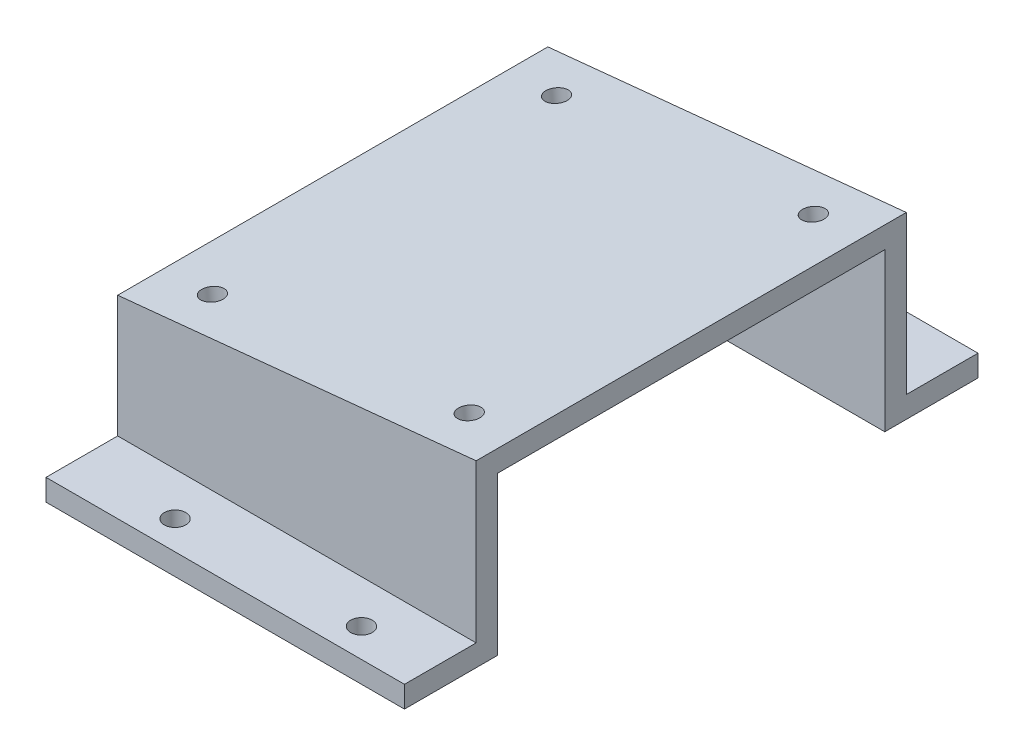
SolidWorks part; units mm, degrees
ref_plane "前视基准面" through (0, 0, 0) normal (0, 0, 1) x (1, 0, 0)
ref_plane "上视基准面" through (0, 0, 0) normal (0, 1, 0) x (1, 0, 0)
ref_plane "右视基准面" through (0, 0, 0) normal (1, 0, 0) x (0, 0, -1)
other "Configuration Table"
sketch "草图4" plane through (0, 0, 0) normal (0, 0, 1) x (1, 0, 0)
  line L0 (0, 0) -> (50, 0)
  line L1 (0, 0) -> (0, 20)
  line L2 (0, 20) -> (50, 25)
  line L3 (50, 25) -> (50, 0)
  dimension "D1" = 50
  dimension "D2" = 25
  dimension "D3" = 20
extrude "凸台-拉伸3" add sketch "草图4" along normal blind 3
sketch "草图5" plane through (0, 0, 3) normal (0, 0, 1) x (1, 0, 0)
  line L0 (0, 20) -> (0, 17)
  line L1 (0, 20) -> (0, 0) construction
  line L2 (0, 17) -> (50, 22)
  line L3 (50, 0) -> (50, 25) construction
  line L4 (50, 22) -> (50, 25)
  line L5 (50, 25) -> (0, 20)
  dimension "D1" = 3
  dimension "D2" = 3
extrude "凸台-拉伸4" add sketch "草图5" along normal blind 54
sketch "草图7" plane through (0, 0, 57) normal (0, 0, 1) x (1, 0, 0)
  line L1 (0, 17) -> (0, 0) construction
  line L2 (0, 0) -> (50, 0) construction
  line L3 (50, 0) -> (50, 22) construction
  line L4 (50, 25) -> (0, 20) construction
  line L5 (0, 20) -> (0, 17) construction
  line L7 (50, 22) -> (50, 25) construction
  line L9 (0, 17) -> (0, 0)
  line L10 (0, 0) -> (50, 0)
  line L11 (50, 0) -> (50, 22)
  line L12 (50, 25) -> (0, 20)
  line L13 (0, 20) -> (0, 17)
  line L15 (50, 22) -> (50, 25)
  line L16 (0, 17) -> (0, 0)
  line L17 (50, 0) -> (50, 22)
sketch "草图8" plane through (0, 0, 57) normal (0, 0, 1) x (1, 0, 0)
  line L0 (0, 20) -> (50, 25)
  line L1 (50, 25) -> (50, 0)
  line L2 (50, 0) -> (0, 0)
  line L3 (0, 0) -> (0, 20)
extrude "凸台-拉伸5" add sketch "草图8" along normal blind 3
sketch "草图9" plane through (0, 0, 60) normal (0, 0, 1) x (1, 0, 0)
  line L0 (0, 0) -> (0, 3)
  line L1 (0, 20) -> (0, 0) construction
  line L2 (0, 3) -> (50, 3)
  line L3 (50, 0) -> (50, 25) construction
  line L4 (50, 3) -> (50, 0)
  line L5 (50, 0) -> (0, 0)
  dimension "D1" = 3
extrude "凸台-拉伸6" add sketch "草图9" along normal blind 10
sketch "草图10" plane through (0, 0, 0) normal (0, 0, -1) x (-1, 0, 0)
  line L0 (-50, 0) -> (0, 0)
  line L1 (0, 0) -> (0, 3)
  line L2 (0, 20) -> (0, 0) construction
  line L3 (0, 3) -> (-50, 3)
  line L4 (-50, 0) -> (-50, 25) construction
  line L5 (-50, 3) -> (-50, 0)
  dimension "D1" = 3
extrude "凸台-拉伸7" add sketch "草图10" along normal blind 10
sketch "草图11" plane through (0, 3, 0) normal (0, 1, 0) x (1, 0, 0)
  line L0 (50, -70) -> (50, -60) construction
  line L2 (50, -60) -> (0, -60) construction
  line L3 (50, -60) -> (0, -60) construction
  line L4 (-23.5358, -30) -> (68.1454, -30) construction
  line L5 (50, 0) -> (0, 0) construction
  circle A0 centre (14, -66) radius 1.5
  circle A1 centre (40, -66) radius 1.5
  circle A2 centre (40, 6) radius 1.5
  circle A3 centre (14, 6) radius 1.5
  dimension "D3" = 3
  dimension "D4" = 3
  dimension "D1" = 36
  dimension "D2" = 6
  dimension "D5" = 10
  dimension "D6" = 6
  dimension "D7" = 30
extrude "切除-拉伸1" cut sketch "草图11" against normal blind 7
sketch "草图12" plane through (-1.9802, 19.802, 0) normal (-0.0995, 0.995, 0) x (0.995, 0.0995, 0)
  line L0 (-11.592, -30) -> (73.4708, -30) construction
  line L1 (27.2395, 11.3677) -> (27.2395, -64.6107) construction
  line L2 (52.2395, -60) -> (1.9901, -60) construction
  line L3 (52.2395, -60) -> (52.2395, 0) construction
  circle A1 centre (45.2395, -6) radius 1.5
  circle A2 centre (45.2395, -54) radius 1.5
  circle A3 centre (9.2395, -54) radius 1.5
  circle A4 centre (9.2395, -6) radius 1.5
  dimension "D1" = 3
  dimension "D4" = 24
  dimension "D2" = 30
  dimension "D3" = 25
  dimension "D5" = 18
extrude "切除-拉伸2" cut sketch "草图12" against normal blind 7
